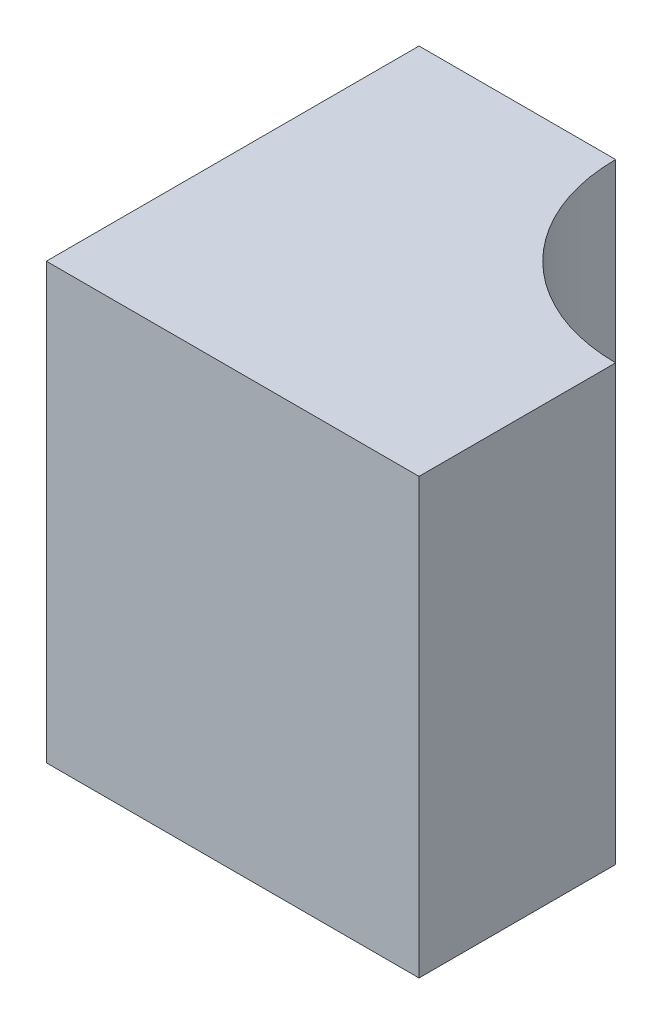
SolidWorks part; units mm, degrees
ref_plane "Front Plane" through (0, 0, 0) normal (0, 0, 1) x (1, 0, 0)
ref_plane "Top Plane" through (0, 0, 0) normal (0, 1, 0) x (1, 0, 0)
ref_plane "Right Plane" through (0, 0, 0) normal (1, 0, 0) x (0, 0, -1)
sketch "Sketch1" plane through (0, 0, 0) normal (0, 1, 0) x (1, 0, 0)
  line L0 (8.8, 16.5) -> (16.5, 16.5) construction
  line L1 (0, 0) -> (16.5, 0) construction
  line L2 (0, 0) -> (0, 16.5) construction
  line L3 (0, 16.5) -> (8.8, 16.5) construction
  line L4 (16.5, 0) -> (16.5, 8.8) construction
  line L5 (8.8, 16.5) -> (0.2, 16.5)
  line L6 (16.5, 8.8) -> (16.5, 0.2)
  line L7 (16.5, 0.2) -> (0.2, 0.2)
  line L8 (0.2, 16.5) -> (0.2, 0.2)
  line L9 (16.5, 16.5) -> (16.5, 8.8) construction
  arc A0 (8.8, 16.5) -> (16.5, 8.8) centre (16.5, 16.5) ccw
  point P8 (8.25, 0)
  dimension "D4" = 15.4
  dimension "D1" = 16.5
  dimension "D2" = 0.2
  dimension "D3" = 0.2
extrude "Boss-Extrude1" add sketch "Sketch1" along normal blind 19
